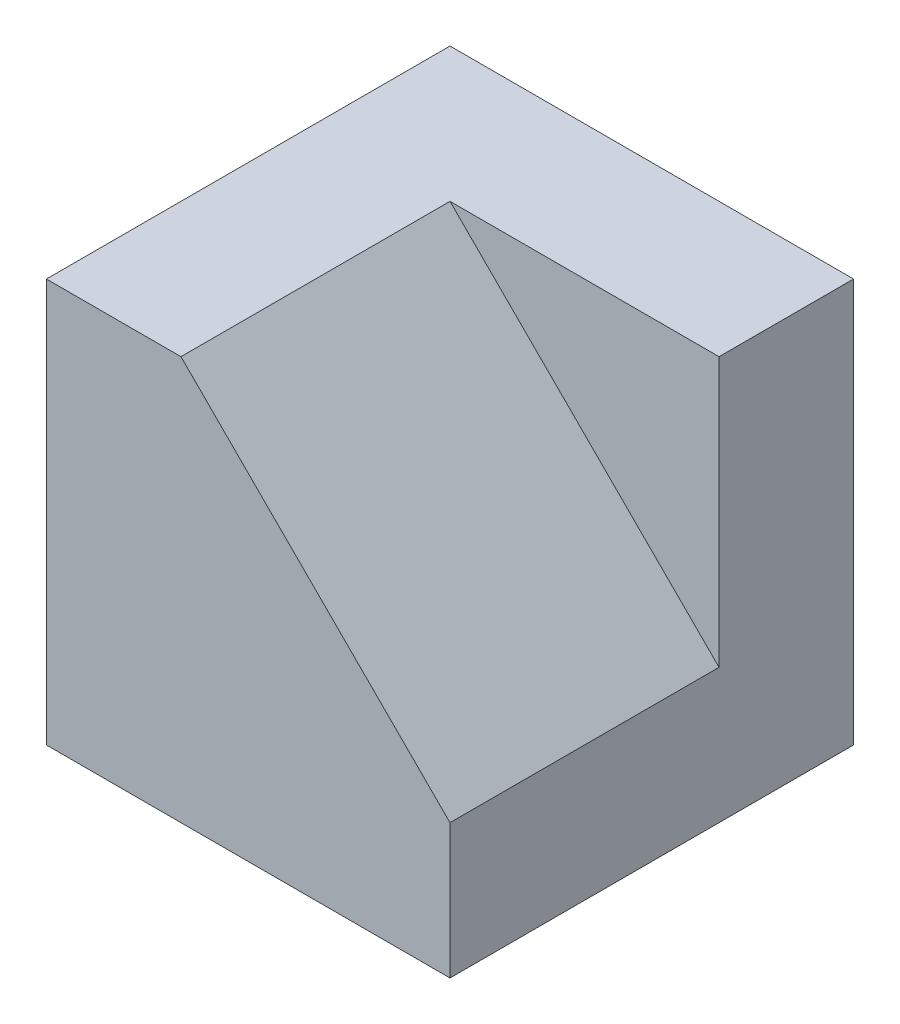
SolidWorks part; units mm, degrees
ref_plane "Plano frontal" through (0, 0, 0) normal (0, 0, 1) x (1, 0, 0)
ref_plane "Plano superior" through (0, 0, 0) normal (0, 1, 0) x (1, 0, 0)
ref_plane "Plano direito" through (0, 0, 0) normal (1, 0, 0) x (0, 0, -1)
sketch "Esboço1" plane through (0, 0, 0) normal (0, 0, 1) x (1, 0, 0)
  line L0 (0, 0) -> (60, 0)
  line L1 (0, 0) -> (0, 60)
  line L2 (0, 60) -> (20, 60)
  line L3 (20, 60) -> (60, 20)
  line L4 (60, 20) -> (60, 0)
  dimension "D1" = 60
  dimension "D2" = 20
  dimension "D3" = 20
  dimension "D4" = 60
extrude "Ressalto-extrusão1" add sketch "Esboço1" along normal blind 40
sketch "Esboço2" plane through (0, 0, 0) normal (0, 0, -1) x (-1, 0, 0)
  line L1 (-60, 0) -> (0, 0)
  line L2 (-60, 0) -> (-60, 60)
  line L3 (-60, 60) -> (0, 60)
  line L4 (0, 0) -> (0, 60)
extrude "Ressalto-extrusão2" add sketch "Esboço2" along normal blind 20
